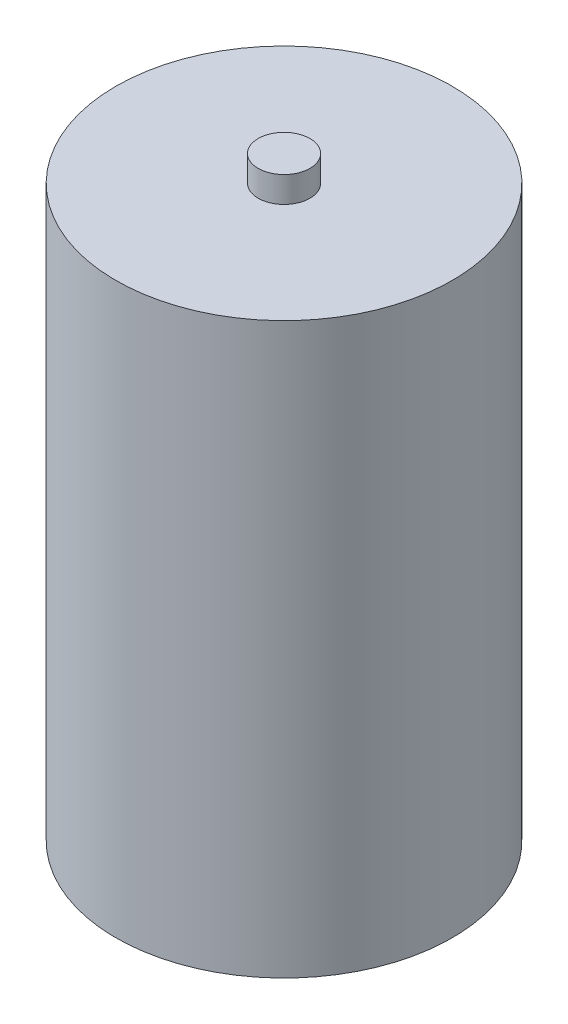
SolidWorks part; units mm, degrees
ref_plane "Alzado" through (0, 0, 0) normal (0, 0, 1) x (1, 0, 0)
ref_plane "Planta" through (0, 0, 0) normal (0, 1, 0) x (1, 0, 0)
ref_plane "Vista lateral" through (0, 0, 0) normal (1, 0, 0) x (0, 0, -1)
sketch "Croquis1" plane through (0, 0, 0) normal (0, 0, 1) x (1, 0, 0)
  line L0 (0, 120) -> (5, 120)
  line L1 (5, 120) -> (5, 115)
  line L2 (5, 115) -> (32.5, 115)
  line L3 (32.5, 115) -> (32.5, 5)
  line L4 (32.5, 5) -> (5, 5)
  line L5 (5, 5) -> (5, 0)
  line L6 (5, 0) -> (0, 0)
  line L7 (0, 120) -> (0, 0)
  dimension "D1" = 5
  dimension "D2" = 32.5
  dimension "D3" = 5
  dimension "D4" = 110
revolve "Revolución1" add sketch "Croquis1" angle 360 about L7
